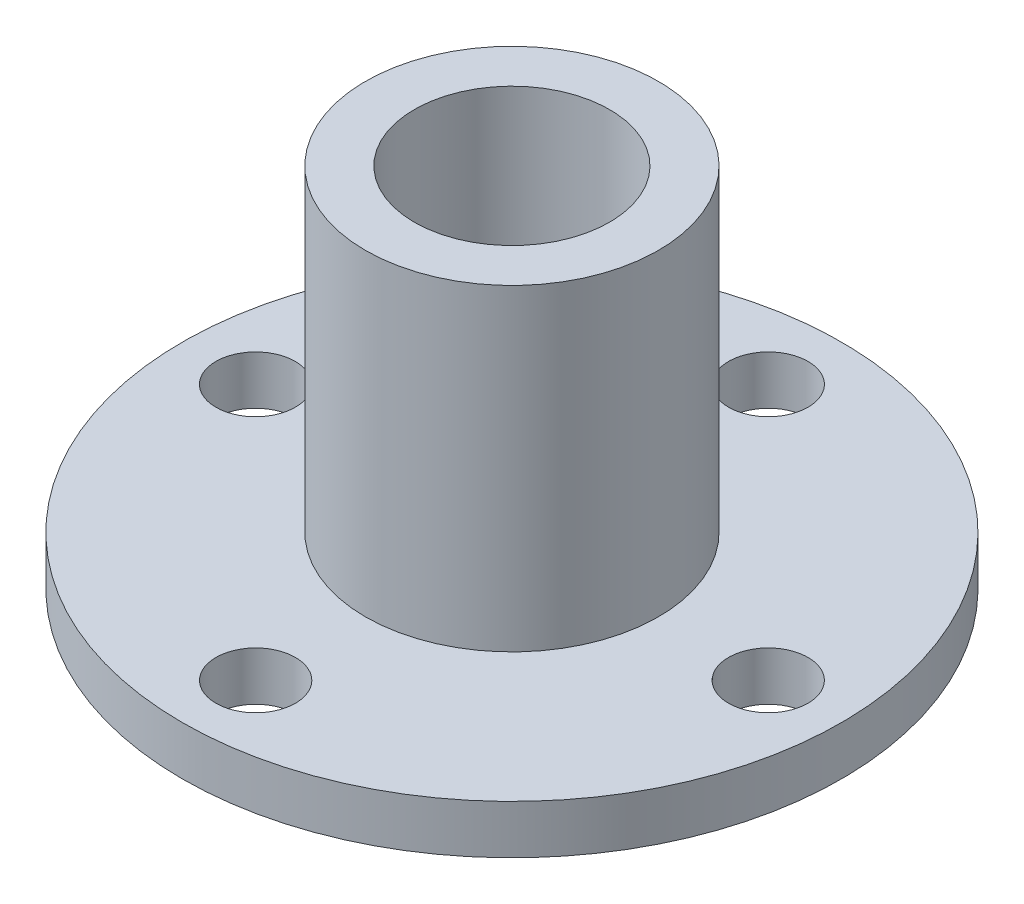
SolidWorks part; units mm, degrees
material "氧化铝"
ref_plane "前视基准面" through (0, 0, 0) normal (0, 0, 1) x (1, 0, 0)
ref_plane "上视基准面" through (0, 0, 0) normal (0, 1, 0) x (1, 0, 0)
ref_plane "右视基准面" through (0, 0, 0) normal (1, 0, 0) x (0, 0, -1)
other "Configuration Table"
sketch "草图1" plane through (0, 0, 0) normal (0, 1, 0) x (1, 0, 0)
  circle A0 centre (0, 0) radius 13.5
  circle A1 centre (0, 0) radius 4
  circle A2 centre (0, 0) radius 6
  circle A3 centre (0, 10.5011) radius 1.6272
  circle A4 centre (10.5, 0) radius 1.6272
  circle A5 centre (0.0021, -10.4989) radius 1.6272
  circle A6 centre (-10.5, 0) radius 1.6272
  dimension "D1" = 21
  dimension "D3" = 27
  dimension "D4" = 2
  dimension "D5" = 8
  dimension "D2" = 21
  dimension "D6" = 14.85
  dimension "D7" = 14.85
  dimension "D8" = 14.85
  dimension "D9" = 14.847
  dimension "D10" = 0
extrude "凸台-拉伸3" add sketch "草图1" along normal blind 2 contours A0 A6 A5 A4 A3 A2 | A2 A1
sketch "草图2" plane through (0, 0, 0) normal (0, 1, 0) x (1, 0, 0)
  circle A0 centre (0, 0) radius 6
  circle A1 centre (0, 0) radius 4
extrude "凸台-拉伸4" add sketch "草图2" along normal blind 15
